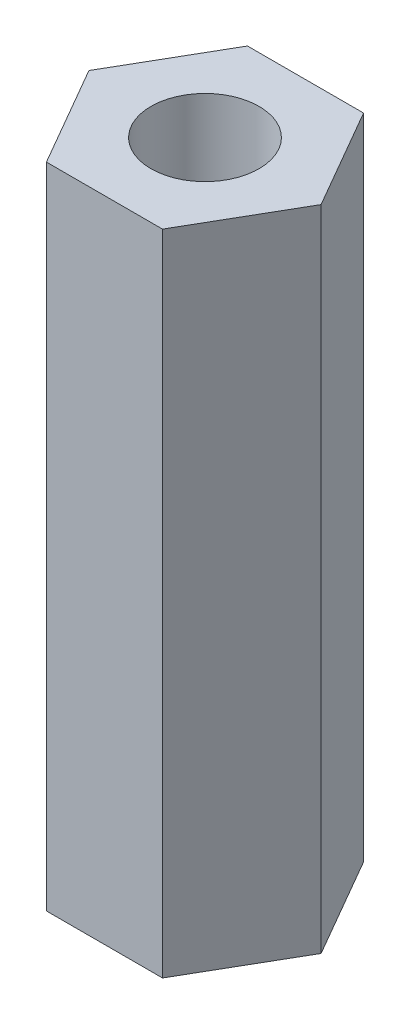
SolidWorks part; units mm, degrees
ref_plane "Front" through (0, 0, 0) normal (0, 0, 1) x (1, 0, 0)
ref_plane "Top" through (0, 0, 0) normal (0, 1, 0) x (1, 0, 0)
ref_plane "Right" through (0, 0, 0) normal (1, 0, 0) x (0, 0, -1)
sketch "Sketch1" plane through (0, 0, 0) normal (0, 1, 0) x (1, 0, 0)
  line L1 (2.6847, 0) -> (1.3423, 2.325)
  line L2 (1.3423, 2.325) -> (-1.3423, 2.325)
  line L3 (-1.3423, 2.325) -> (-2.6847, 0)
  line L4 (-2.6847, 0) -> (-1.3423, -2.325)
  line L5 (-1.3423, -2.325) -> (1.3423, -2.325)
  line L6 (1.3423, -2.325) -> (2.6847, 0)
  circle A0 centre (0, 0) radius 2.325 construction
  dimension "D1" = 4.65
extrude "base" add sketch "Sketch1" along normal blind 15
sketch "Sketch2" plane through (0, 15, 0) normal (0, 1, 0) x (1, 0, 0)
  circle A0 centre (0, 0) radius 1.25
  dimension "D1" = 2.5
extrude "hole" cut sketch "Sketch2" against normal through all both and the other way through all
